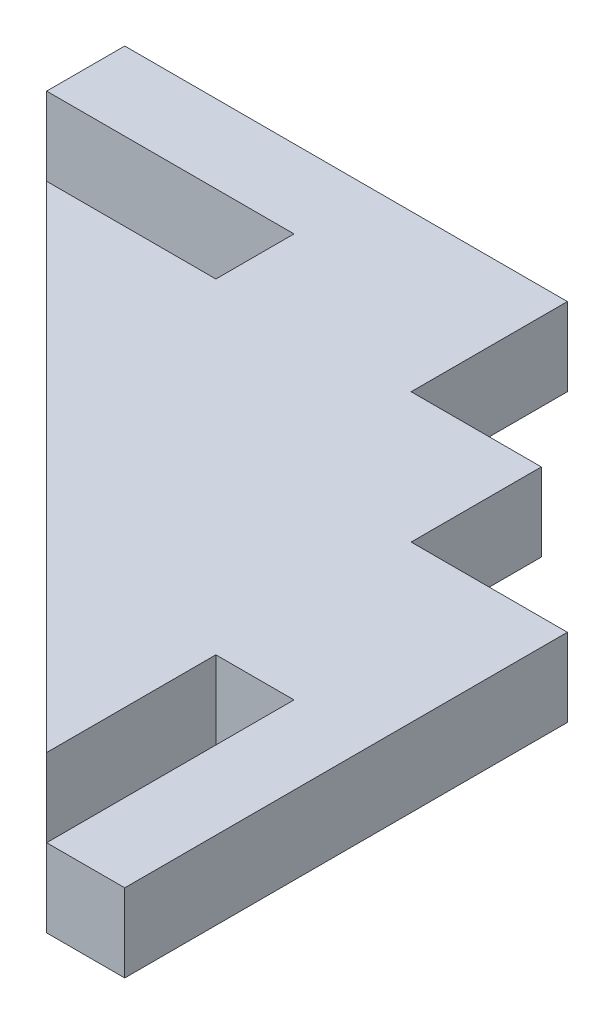
SolidWorks part; units mm, degrees
ref_plane "Front" through (0, 0, 0) normal (0, 0, 1) x (1, 0, 0)
ref_plane "Top" through (0, 0, 0) normal (0, 1, 0) x (1, 0, 0)
ref_plane "Right" through (0, 0, 0) normal (1, 0, 0) x (0, 0, -1)
sketch "Sketch2" plane through (0, 0, 0) normal (0, 1, 0) x (1, 0, 0)
  line L0 (0, 0) -> (-10, 0)
  line L1 (-50, 12) -> (12, -50)
  line L2 (0, -10) -> (0, 0)
  line L3 (-10, 0) -> (-10, 12)
  line L4 (-10, 12) -> (-50, 12)
  line L7 (12, -50) -> (12, -10)
  line L8 (12, -10) -> (0, -10)
  point P6 (0, 0)
  point P10 (6, -34.6797)
  point P11 (0, 0)
  point P12 (0, 0)
  point P13 (0, 0)
  dimension "D1" = 12
  dimension "D3" = 50
  dimension "D4" = 10
extrude "Boss-Extrude1" add sketch "Sketch2" along normal blind 6
sketch "Sketch3" plane through (0, 6, 0) normal (0, 1, 0) x (1, 0, 0)
  line L0 (-50, 12) -> (12, -50) construction
  line L1 (-44, 6) -> (-25, 6)
  line L2 (-44, 6) -> (-44, 0)
  line L3 (-44, 0) -> (-25, 0)
  line L4 (-25, 6) -> (-25, 0)
  line L5 (0, 0) -> (-10, 0) construction
  line L6 (6, -44) -> (0, -44)
  line L7 (6, -44) -> (6, -25)
  line L8 (6, -25) -> (0, -25)
  line L9 (0, -44) -> (0, -25)
  line L10 (0, -10) -> (0, 0) construction
  dimension "D1" = 6
  dimension "D2" = 25
extrude "Cut-Extrude1" cut sketch "Sketch3" against normal through all
sketch "Sketch4" plane through (0, 6, 0) normal (0, 1, 0) x (1, 0, 0)
  line L1 (-44, 6) -> (-50, 6)
  line L2 (-44, 6) -> (-44, 12)
  line L3 (-44, 12) -> (-50, 12)
  line L4 (-50, 6) -> (-50, 12)
  line L5 (6, -44) -> (12, -44)
  line L6 (6, -44) -> (6, -50)
  line L7 (6, -50) -> (12, -50)
  line L8 (12, -44) -> (12, -50)
extrude "Cut-Extrude2" cut sketch "Sketch4" against normal through all
